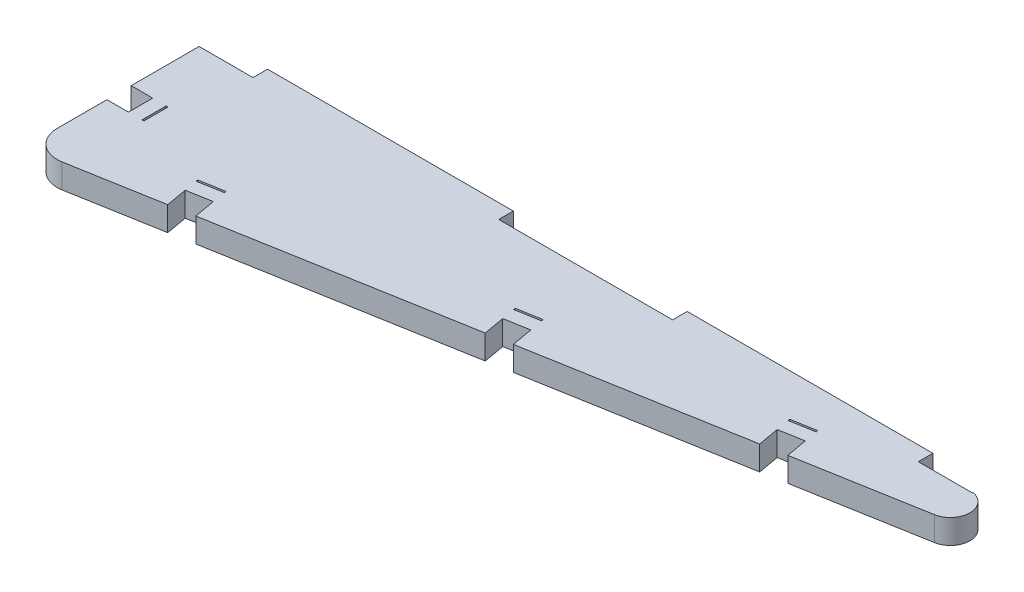
SolidWorks part; units mm, degrees
ref_plane "Front Plane" through (0, 0, 0) normal (0, 0, 1) x (1, 0, 0)
ref_plane "Top Plane" through (0, 0, 0) normal (0, 1, 0) x (1, 0, 0)
ref_plane "Right Plane" through (0, 0, 0) normal (1, 0, 0) x (0, 0, -1)
sketch "Sketch1" plane through (0, 0, 0) normal (0, 1, 0) x (1, 0, 0)
  line L0 (-112.6247, 140.9649) -> (-67.0623, 140.9649)
  line L1 (-112.6247, 140.9649) -> (-112.6247, 138.2649)
  line L2 (-112.6247, 138.2649) -> (-122.6247, 138.2649)
  line L3 (-122.6247, 138.2649) -> (-122.6247, 125.6711)
  line L4 (-116.7565, 107.0198) -> (-100.1289, 109.9517)
  line L5 (20.7445, 131.2649) -> (20.7445, 138.4007) construction
  line L6 (20.7445, 138.2649) -> (10.7445, 138.2649)
  line L7 (10.7445, 138.2649) -> (10.7445, 140.9649)
  line L8 (-34.8179, 140.9649) -> (10.7445, 140.9649)
  line L9 (-34.8179, 138.2649) -> (-67.0623, 138.2649)
  line L10 (-34.8179, 138.2649) -> (-34.8179, 140.9649)
  line L11 (-130.3423, 140.9649) -> (-130.3423, 138.2649) construction
  line L12 (-67.0623, 138.2649) -> (-67.0623, 140.9649)
  line L13 (-112.6247, 140.9649) -> (-67.0623, 140.9649) construction
  line L14 (-34.8179, 140.9649) -> (-34.8179, 138.2649) construction
  line L15 (-45.647, 119.5583) -> (-46.3416, 123.4975)
  line L16 (10.7445, 140.9649) -> (10.7445, 138.2649) construction
  line L17 (-50.0786, 118.7769) -> (-50.7732, 122.7161)
  line L18 (-2.3819, 127.1871) -> (-3.0765, 131.1263)
  line L19 (-6.8136, 126.4057) -> (-7.5082, 130.3449)
  line L20 (-3.0765, 131.1263) -> (-7.5082, 130.3449)
  line L21 (-2.3819, 127.1871) -> (20.7445, 131.2649)
  line L22 (-46.3416, 123.4975) -> (-50.7732, 122.7161)
  line L23 (-122.6247, 121.1711) -> (-118.6247, 121.1711)
  line L24 (-95.6973, 110.7331) -> (-96.3919, 114.6723)
  line L25 (-100.1289, 109.9517) -> (-100.8235, 113.8909)
  line L26 (-96.3919, 114.6723) -> (-100.8235, 113.8909)
  line L27 (-45.647, 119.5583) -> (-6.8136, 126.4057)
  line L28 (-122.6247, 125.6711) -> (-118.6247, 125.6711)
  line L29 (-95.6973, 110.7331) -> (-50.0786, 118.7769)
  line L30 (-118.6247, 121.1711) -> (-118.6247, 125.6711)
  line L31 (-122.6247, 121.1711) -> (-122.6247, 111.9438)
  line L32 (-3.5107, 133.5883) -> (-7.9423, 132.8069)
  line L33 (-3.5107, 133.5883) -> (-3.5714, 133.933)
  line L34 (20.7445, 138.4007) -> (20.7445, 138.2649)
  line L35 (7.4801, 168.2649) -> (-101.7148, 168.2649) construction
  line L36 (-7.9423, 132.8069) -> (-8.0031, 133.1516)
  line L37 (-3.5714, 133.933) -> (-8.0031, 133.1516)
  line L38 (-46.7757, 125.9595) -> (-51.2074, 125.1781)
  line L39 (-46.7757, 125.9595) -> (-46.8365, 126.3042)
  line L40 (-51.2074, 125.1781) -> (-51.2681, 125.5228)
  line L41 (-46.8365, 126.3042) -> (-51.2681, 125.5228)
  line L42 (-96.7911, 117.1405) -> (-101.2576, 116.3529)
  line L43 (-96.7911, 117.1405) -> (-96.8519, 117.4852)
  line L44 (-101.2576, 116.3529) -> (-101.3184, 116.6976)
  line L45 (-96.8519, 117.4852) -> (-101.3184, 116.6976)
  line L46 (-115.7747, 125.6711) -> (-115.7747, 121.1711)
  line L47 (-115.7747, 125.6711) -> (-116.1247, 125.6711)
  line L48 (-115.7747, 121.1711) -> (-116.1247, 121.1711)
  line L49 (-116.1247, 125.6711) -> (-116.1247, 121.1711)
  arc A0 (20.7445, 131.2649) -> (20.7445, 138.4007) centre (20.1154, 134.8328) ccw
  arc A1 (-122.6247, 111.9438) -> (-116.7565, 107.0198) centre (-117.6247, 111.9438) ccw
  dimension "D4" = 5
  dimension "D9" = 0.35
  dimension "D10" = 2.5
  dimension "D1" = 10
  dimension "D2" = 10
  dimension "D3" = 4.5
  dimension "D5" = 7
  dimension "D6" = 4
  dimension "D7" = 30
  dimension "D8" = 10
  dimension "D11" = 2.5
  dimension "D12" = 2.5
  dimension "D13" = 2.5
  dimension "D14" = 0.35
  dimension "D15" = 0.35
  dimension "D16" = 0.35
extrude "Boss-Extrude1" add sketch "Sketch1" along normal blind 4.5
